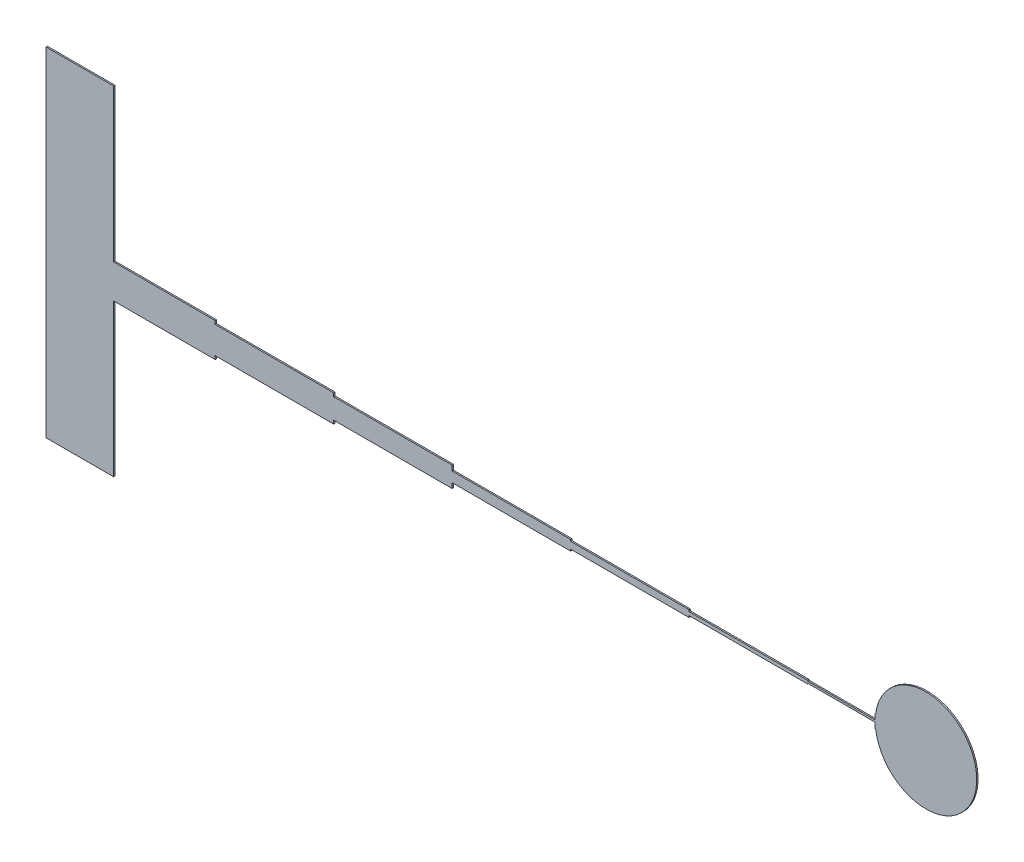
SolidWorks part; units mm, degrees
ref_plane "Front Plane" through (0, 0, 0) normal (0, 0, 1) x (1, 0, 0)
ref_plane "Top Plane" through (0, 0, 0) normal (0, 1, 0) x (1, 0, 0)
ref_plane "Right Plane" through (0, 0, 0) normal (1, 0, 0) x (0, 0, -1)
sketch "Sketch1" plane through (0, 0, 0) normal (0, 0, 1) x (1, 0, 0)
  line L0 (1000, 250) -> (5000, 250)
  line L1 (-1000, 2500) -> (1000, 2500)
  line L2 (-1000, 2500) -> (-1000, -2500)
  line L3 (-1000, -2500) -> (1000, -2500)
  line L4 (1000, 2500) -> (1000, 250)
  line L5 (-1000, 2500) -> (1000, -2500) construction
  line L6 (-1000, -2500) -> (1000, 2500) construction
  line L9 (1000, -250) -> (5000, -250)
  line L10 (5000, 250) -> (5000, 125)
  line L11 (-3000, 250) -> (5000, -250) construction
  line L12 (-3000, -250) -> (5000, 250) construction
  line L13 (5000, 125) -> (9000, 125)
  line L15 (5000, -125) -> (9000, -125)
  line L16 (9000, 125) -> (9000, 100)
  line L17 (1000, 125) -> (9000, -125) construction
  line L18 (1000, -125) -> (9000, 125) construction
  line L19 (9000, 100) -> (11256.6966, 100)
  line L21 (9000, -100) -> (11256.6966, -100)
  line L23 (6000, 100) -> (12000, -100) construction
  line L24 (6000, -100) -> (12000, 100) construction
  line L25 (1000, -250) -> (1000, -2500)
  line L26 (5000, -125) -> (5000, -250)
  line L27 (9000, -100) -> (9000, -125)
  arc A0 (11256.6966, -100) -> (11256.6966, 100) centre (12000, 0) ccw
  point P0 (0, 0)
  point P6 (1000, 0)
  point P11 (5000, 0)
  point P16 (9000, 0)
  dimension "D9" = 1500
  dimension "D1" = 2000
  dimension "D2" = 5000
  dimension "D3" = 500
  dimension "D4" = 4000
  dimension "D5" = 250
  dimension "D6" = 4000
  dimension "D7" = 200
extrude "Boss-Extrude1" add sketch "Sketch1" against normal blind 20
sketch "Sketch2" plane through (0, 0, 0) normal (0, 0, 1) x (1, 0, 0)
  line L0 (0, -11) -> (0, 11) construction
  line L1 (1000, 2500) -> (0, 2500)
  line L2 (1000, 2500) -> (1000, 250)
  line L3 (1000, 250) -> (0, 250)
  line L4 (0, 2500) -> (0, 250)
  line L5 (1000, -2500) -> (0, -2500)
  line L6 (1000, -2500) -> (1000, -250)
  line L7 (1000, -250) -> (0, -250)
  line L8 (0, -2500) -> (0, -250)
  dimension "D1" = 1000
  dimension "D2" = 2250
extrude "Cut-Extrude1" cut sketch "Sketch2" against normal through all
sketch "Sketch3" plane through (0, 0, 0) normal (0, 0, 1) x (1, 0, 0)
  line L0 (0, 0) -> (1098.3807, 0) construction
  line L1 (11, 0) -> (-11, 0) construction
  line L2 (5000, 250) -> (0, 250) construction
  line L3 (1500, 250) -> (3250, 250)
  line L4 (1500, 250) -> (1500, 200)
  line L5 (1500, 200) -> (3250, 200)
  line L7 (0, -250) -> (5000, -250) construction
  line L8 (1500, -250) -> (3250, -250)
  line L9 (1500, -250) -> (1500, -200)
  line L10 (1500, -200) -> (3250, -200)
  line L12 (0, -11) -> (0, 11) construction
  line L13 (3250, 200) -> (3250, 150)
  line L14 (3250, 250) -> (5000, 250)
  line L16 (3250, 150) -> (5000, 150)
  line L17 (5000, 250) -> (5000, 150)
  line L18 (3250, -250) -> (5000, -250)
  line L19 (3250, -200) -> (3250, -150)
  line L20 (3250, -150) -> (5000, -150)
  line L21 (5000, -250) -> (5000, -150)
  point P17 (1500, 225)
  dimension "D1" = 1098.3807
  dimension "D2" = 1750
  dimension "D3" = 50
  dimension "D4" = 1750
  dimension "D5" = 50
  dimension "D6" = 1500
  dimension "D7" = 1500
  dimension "D8" = 100
  dimension "D9" = 100
  dimension "D10" = 1750
  dimension "D11" = 1750
extrude "Cut-Extrude4" cut sketch "Sketch3" against normal through all contours L8 L18 L21 L20 L19 L10 L9
mirror "Mirror1" about plane through (0, 0, 0) normal (0, 1, 0) of "Cut-Extrude4"
sketch "Sketch4" plane through (0, 0, 0) normal (0, 0, 1) x (1, 0, 0)
  line L1 (5000, 125) -> (6750, 125)
  line L2 (5000, 125) -> (5000, 75)
  line L3 (5000, 75) -> (6750, 75)
  line L4 (6750, 125) -> (6750, 75)
  dimension "D1" = 1750
  dimension "D2" = 50
extrude "Cut-Extrude5" cut sketch "Sketch4" against normal through all
mirror "Mirror2" about plane through (0, 0, 0) normal (0, 1, 0) of "Cut-Extrude5"
sketch "Sketch5" plane through (0, 0, 0) normal (0, 0, 1) x (1, 0, 0)
  line L1 (6750, 125) -> (8500, 125)
  line L2 (6750, 125) -> (6750, 50)
  line L3 (6750, 50) -> (8500, 50)
  line L4 (8500, 125) -> (8500, 50)
  dimension "D1" = 1750
  dimension "D2" = 75
extrude "Cut-Extrude6" cut sketch "Sketch5" against normal through all
mirror "Mirror3" about plane through (0, 0, 0) normal (0, 1, 0) of "Cut-Extrude6"
sketch "Sketch6" plane through (0, 0, 0) normal (0, 0, 1) x (1, 0, 0)
  line L1 (8500, 125) -> (10250, 125)
  line L2 (8500, 125) -> (8500, 25)
  line L3 (8500, 25) -> (10250, 25)
  line L4 (10250, 125) -> (10250, 25)
  dimension "D1" = 1750
  dimension "D2" = 100
extrude "Cut-Extrude7" cut sketch "Sketch6" against normal through all
mirror "Mirror4" about plane through (0, 0, 0) normal (0, 1, 0) of "Cut-Extrude7"
sketch "Sketch7" plane through (0, 0, 0) normal (0, 0, 1) x (1, 0, 0)
  line L1 (10250, 100) -> (11250, 100)
  line L2 (10250, 100) -> (10250, 15)
  line L3 (10250, 15) -> (11250, 15)
  line L4 (11250, 100) -> (11250, 15)
  dimension "D1" = 1000
  dimension "D2" = 85
extrude "Cut-Extrude8" cut sketch "Sketch7" against normal through all
mirror "Mirror5" about plane through (0, 0, 0) normal (0, 1, 0) of "Cut-Extrude8"
